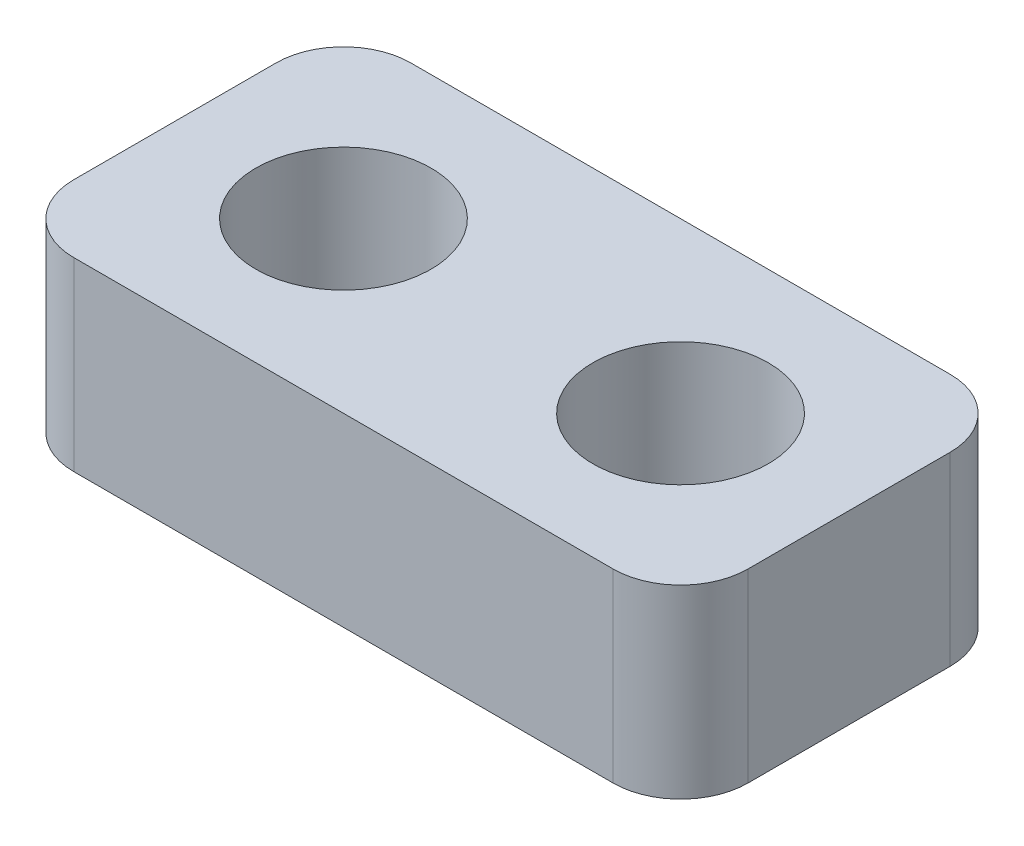
SolidWorks part; units mm, degrees
ref_plane "Front Plane" through (0, 0, 0) normal (0, 0, 1) x (1, 0, 0)
ref_plane "Top Plane" through (0, 0, 0) normal (0, 1, 0) x (1, 0, 0)
ref_plane "Right Plane" through (0, 0, 0) normal (1, 0, 0) x (0, 0, -1)
sketch "Sketch1" plane through (0, 0, 0) normal (0, 1, 0) x (1, 0, 0)
  line L0 (10, 10) -> (10, 0) construction
  line L1 (0, 0) -> (20, 0)
  line L2 (0, 0) -> (0, 10)
  line L3 (0, 10) -> (20, 10)
  line L4 (20, 0) -> (20, 10)
  circle A0 centre (5, 5) radius 2.6
  circle A1 centre (15, 5) radius 2.6
  point P9 (0, 0)
  point P10 (10, 5)
  dimension "D3" = 5.2
  dimension "D1" = 10
  dimension "D2" = 20
  dimension "D4" = 5
extrude "Boss-Extrude1" add sketch "Sketch1" along normal blind 5.5
fillet "Fillet1" radius 2 4 edges at (0, 2.75, -10) (20, 2.75, -10) (0, 2.75, 0) (20, 2.75, 0)
